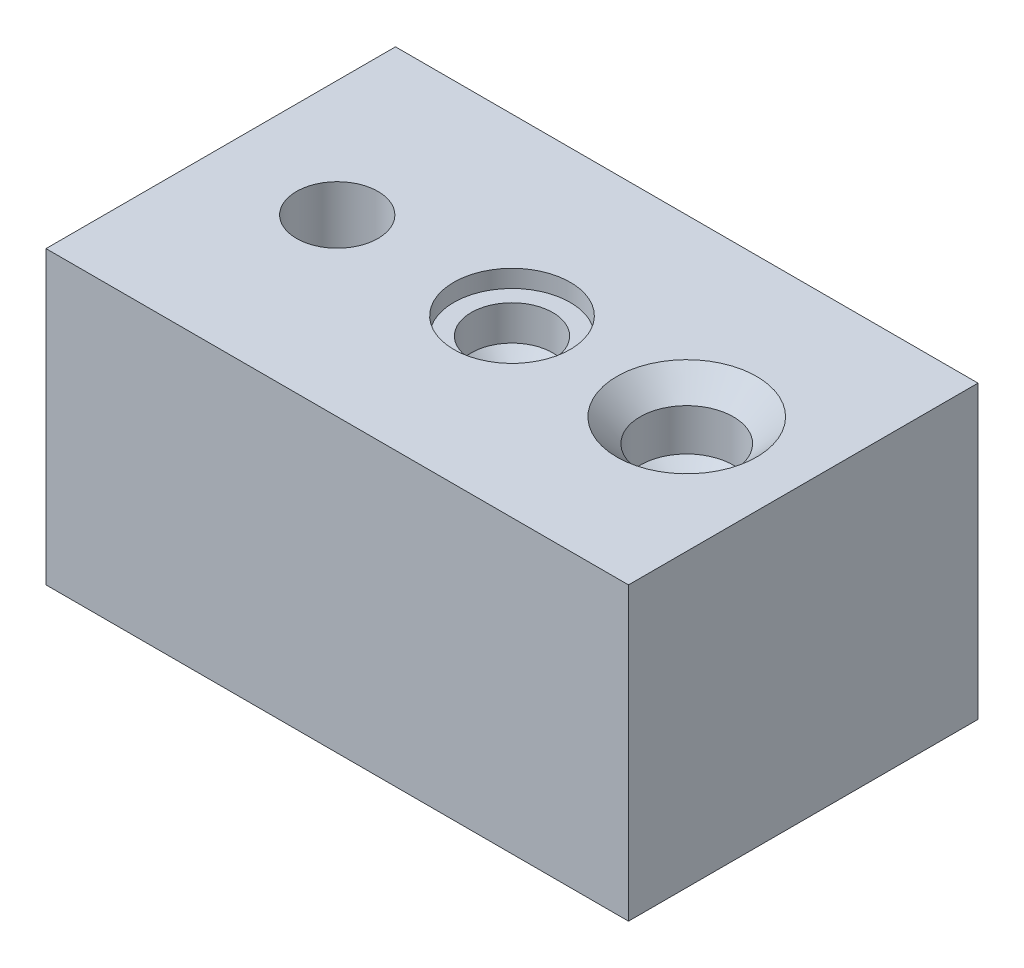
SolidWorks part; units mm, degrees
ref_plane "Plano frontal" through (0, 0, 0) normal (0, 0, 1) x (1, 0, 0)
ref_plane "Plano superior" through (0, 0, 0) normal (0, 1, 0) x (1, 0, 0)
ref_plane "Plano direito" through (0, 0, 0) normal (1, 0, 0) x (0, 0, -1)
sketch "Esboço2" plane through (0, 0, 0) normal (0, 1, 0) x (1, 0, 0)
  line L1 (0, 0) -> (-100, 0)
  line L2 (0, 0) -> (0, 60)
  line L3 (0, 60) -> (-100, 60)
  line L4 (-100, 0) -> (-100, 60)
  dimension "D1" = 100
  dimension "D2" = 60
extrude "Ressalto-extrusão1" add sketch "Esboço2" along normal blind 50
hole_wizard "Furo1" positions "Esboço3" profile "Esboço5" legacy
sketch "Esboço3" plane through (0, 50, 0) normal (0, 1, 0) x (1, 0, 0)
  line L0 (0, 0) -> (0, 60) construction
  line L1 (-100, 0) -> (0, 0) construction
  point P0 (-50, 30)
  point P9 (-47.8582, 23.7444)
  dimension "D1" = 50
  dimension "D2" = 30
sketch "Esboço5" plane through (-50, 50, -30) normal (1, 0, 0) x (0, 0, 1)
  line L0 (0, 0) -> (0, 16)
  line L1 (0, 16) -> (7, 9)
  line L2 (7, 9) -> (7, 3)
  line L3 (7, 3) -> (10, 3)
  line L4 (10, 0) -> (0, 0)
  line L5 (0, -11.3109) -> (0, 121.1557) construction
  line L6 (0, 16) -> (-7, 9) construction
  line L7 (10, 3) -> (10, 0)
  dimension "Depth" = 16
  dimension "Drill Angle" = 90
  dimension "Diameter" = 14
  dimension "C-Bore Diameter" = 20
  dimension "C-Bore Depth" = 3
hole_wizard "Furo2" positions "Esboço9" profile "Esboço11" legacy
sketch "Esboço9" plane through (0, 50, 0) normal (0, 1, 0) x (1, 0, 0)
  line L0 (0, 60) -> (-100, 60) construction
  line L1 (0, 0) -> (0, 60) construction
  point P0 (-20, 30)
  dimension "D1" = 30
  dimension "D2" = 20
sketch "Esboço11" plane through (-20, 50, -30) normal (1, 0, 0) x (0, 0, 1)
  line L0 (0, 0) -> (0, 16)
  line L1 (0, 16) -> (8, 11.1931)
  line L2 (8, 11.1931) -> (8, 4)
  line L3 (8, 4) -> (12, 0)
  line L4 (12, 0) -> (0, 0)
  line L5 (0, -14.3089) -> (0, 102.4216) construction
  line L6 (0, 16) -> (-8, 11.1931) construction
  line L7 (-8, 4) -> (-12, 0) construction
  dimension "Diameter" = 16
  dimension "Depth" = 16
  dimension "C-Sink Diameter" = 24
  dimension "C-Sink Angle" = 90
  dimension "Drill Angle" = 118
hole_wizard "Broca de rosquear para tarraxa de M16x2.02" positions "Esboço17" profile "Esboço18" hole size "M16x2.0" standard "Ansi Metric" end condition through all
sketch "Esboço17" plane through (0, 50, 0) normal (0, 1, 0) x (1, 0, 0)
  line L0 (-100, 60) -> (-100, 0) construction
  line L2 (0, 60) -> (-100, 60) construction
  point P0 (-80, 30)
  dimension "D1" = 20
  dimension "D2" = 30
sketch "Esboço18" plane through (-80, 50, -30) normal (1, 0, 0) x (0, 0, 1)
  line L0 (0, 0) -> (0, 50)
  line L1 (0, 50) -> (7, 50)
  line L2 (7, 50) -> (7, 0)
  line L5 (7, 0) -> (0, 0)
  line L11 (0, -6.35) -> (0, 107.95) construction
  dimension "Thru Hole Dia." = 14
  dimension "Thru Hole Depth" = 50
